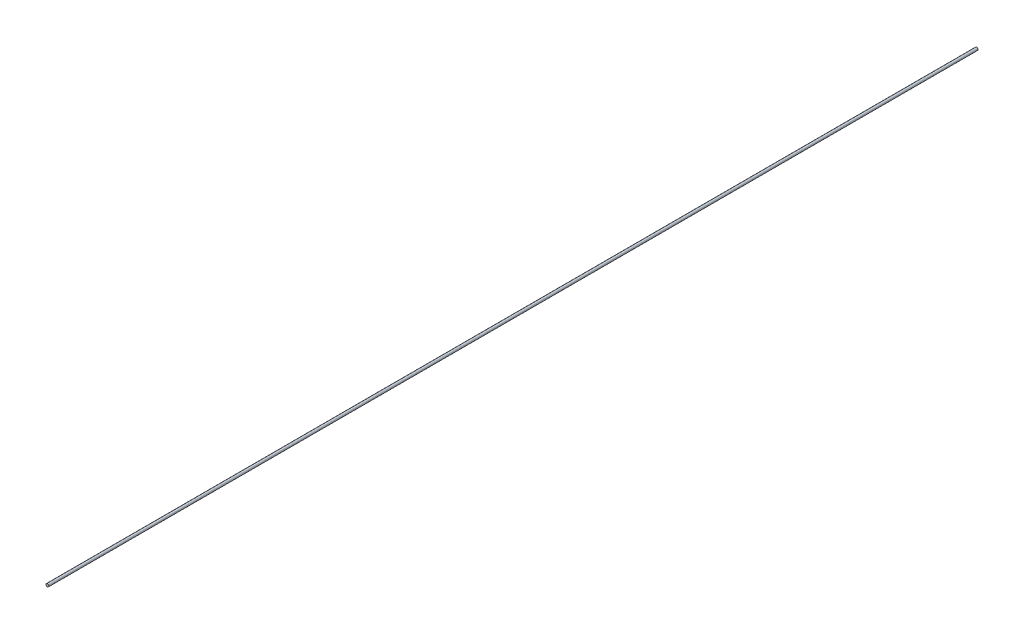
SolidWorks part; units mm, degrees
material "AISI 1015 Aço, trefilado (SS)"
ref_plane "Plano frontal" through (0, 0, 0) normal (0, 0, 1) x (1, 0, 0)
ref_plane "Plano superior" through (0, 0, 0) normal (0, 1, 0) x (1, 0, 0)
ref_plane "Plano direito" through (0, 0, 0) normal (1, 0, 0) x (0, 0, -1)
sketch "Esboço1" plane through (0, 0, 0) normal (0, 0, 1) x (1, 0, 0)
  circle A0 centre (0, 0) radius 5
  dimension "D1" = 10
extrude "Ressalto-extrusão1" add sketch "Esboço1" along normal mid plane 3350 contours A0
